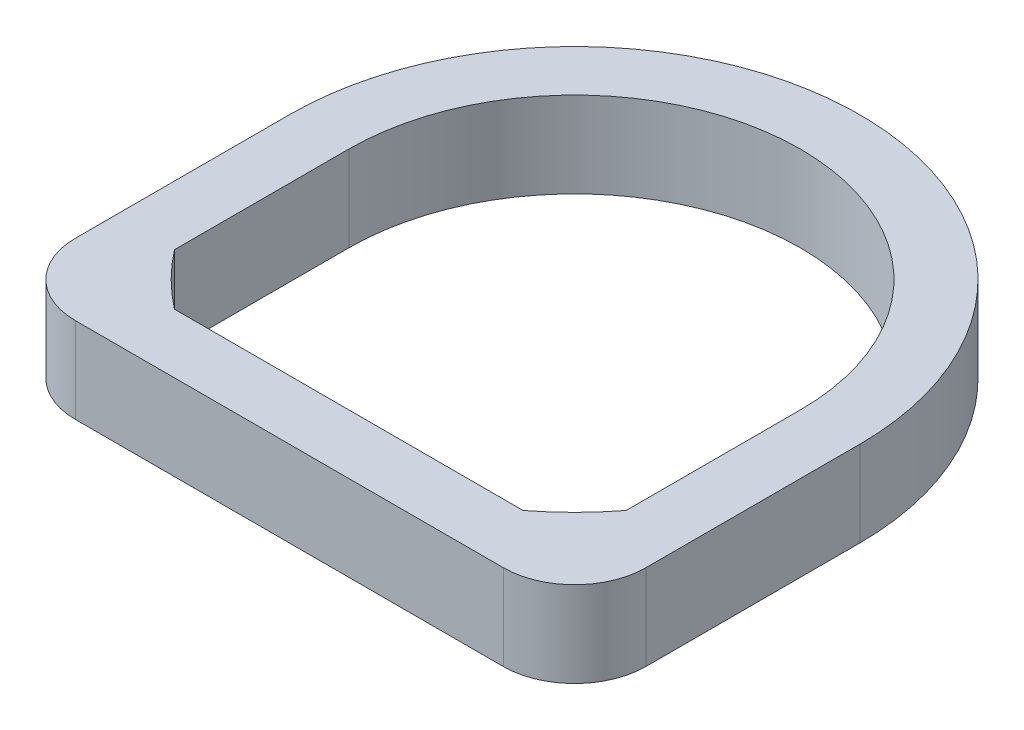
SolidWorks part; units mm, degrees
ref_plane "Front Plane" through (0, 0, 0) normal (0, 0, 1) x (1, 0, 0)
ref_plane "Top Plane" through (0, 0, 0) normal (0, 1, 0) x (1, 0, 0)
ref_plane "Right Plane" through (0, 0, 0) normal (1, 0, 0) x (0, 0, -1)
sketch "Sketch1" plane through (0, 0, 0) normal (0, 1, 0) x (1, 0, 0)
  line L0 (-7.9165, 0) -> (7.9165, 0)
  line L1 (-7.9165, 0) -> (-7.9165, -7.9165)
  line L2 (-7.9165, -7.9165) -> (7.9165, -7.9165)
  line L3 (7.9165, 0) -> (7.9165, -7.9165)
  line L4 (0, -7.9165) -> (0, 6.8656) construction
  line L5 (5.9165, -7.9165) -> (7.9165, -5.9165)
  line L6 (7.9165, -7.9165) -> (7.9165, -5.9165)
  line L7 (7.9165, -7.9165) -> (5.9165, -7.9165)
  line L8 (7.9165, -7.9165) -> (7.9165, -5.9165)
  line L9 (-5.9165, -7.9165) -> (-7.9165, -5.9165)
  line L11 (-10, 0) -> (10, 0)
  line L12 (-10, 0) -> (-10, -10)
  line L13 (-10, -10) -> (10, -10)
  line L14 (10, 0) -> (10, -10)
  circle A0 centre (0, 0) radius 7.9165
  circle A1 centre (0, 0) radius 10
  point P6 (7.9165, -7.9165)
extrude "Boss-Extrude1" add sketch "Sketch1" along normal blind 3 contours L11 A1 A0 | L11 A1 L1 | A1 L12 L13 L2 L1 | A1 L2 | A1 L8 L7 L13 L14 | L3 A1 L11 | A1 L7 L8 | A1 L1 L2
fillet "Fillet1" radius 2.5 2 edges at (10, 1.5, 10) (-10, 1.5, 10)
